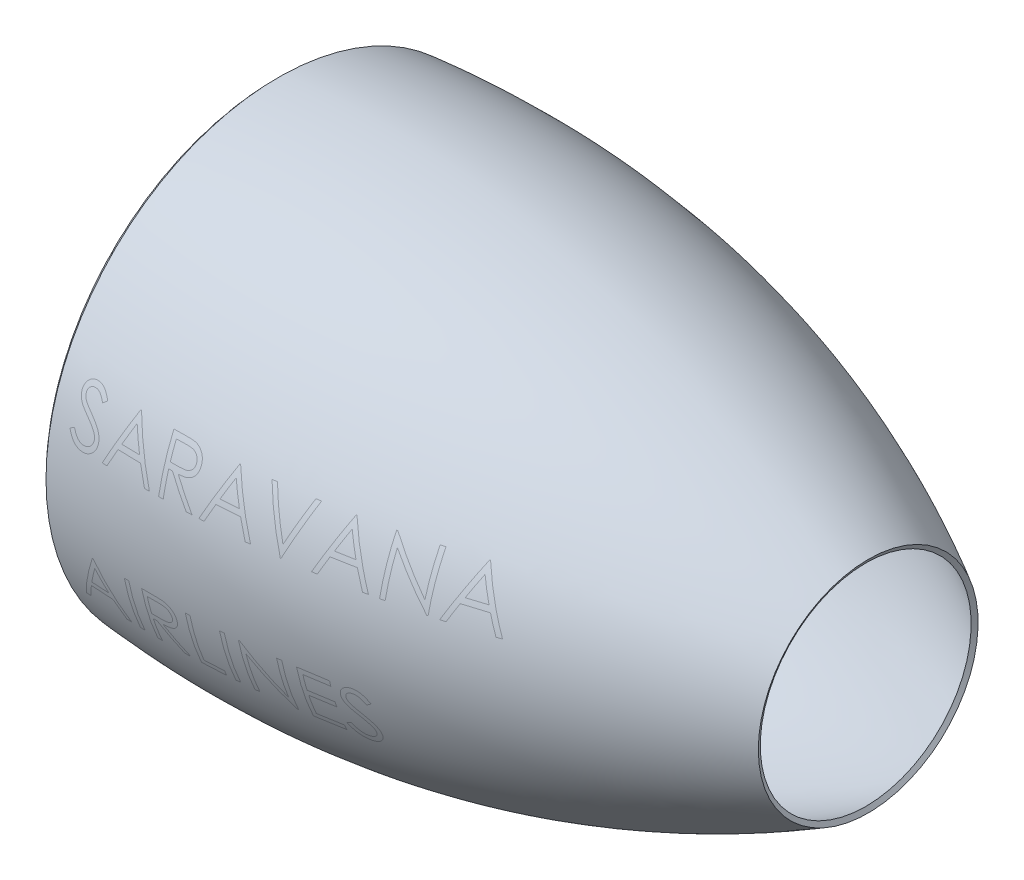
SolidWorks part; units mm, degrees
ref_plane "Front Plane" through (0, 0, 0) normal (0, 0, 1) x (1, 0, 0)
ref_plane "Top Plane" through (0, 0, 0) normal (0, 1, 0) x (1, 0, 0)
ref_plane "Right Plane" through (0, 0, 0) normal (1, 0, 0) x (0, 0, -1)
sketch "Sketch1" plane through (0, 0, 0) normal (0, 0, 1) x (1, 0, 0)
  line L0 (621.6787, 0) -> (0, 0) construction
  line L1 (0, 0) -> (0, 228.1541) construction
  line L2 (0, 180) -> (25, 180)
  line L3 (25, 180) -> (44.8479, 190)
  line L4 (44.8479, 190) -> (69.8479, 190)
  spline S0 degree 2 poles (0, 228.1541) (313.0954, 257.5885) (580, 108) knots 0 0 0 1 1 1
  spline S1 degree 2 poles (0, 228.1541) (-24.4685, 203.728) (0, 180) knots 0 0 0 1 1 1
  point P6 (-19.8945, 215.3986)
  point P12 (0, 228.1541)
  point P13 (-12.2246, 203.227)
  point P14 (390.041, 190)
  point P15 (44.8479, 190)
  dimension "D1" = 580
  dimension "D2" = 108
  dimension "D3" = 180
  dimension "D4" = 190
  dimension "D5" = 25
  dimension "D6" = 25
surface "Surface-Revolve1" sketch "Sketch1" parameters "D1"=360
thicken "Thicken1" surfaces to thicken 101 thickness 5 parameters "D1"=5
ref_plane "Plane1" through (0, 0, 250) normal (0, 0, 1) x (1, 0, 0)
sketch "Sketch2" plane through (0, 0, 250) normal (0, 0, 1) x (1, 0, 0)
  line L0 (18.0638, 41.8491) -> (534.2023, 41.8491) construction
  line L1 (18.0638, -95.3229) -> (534.2023, -95.3229) construction
  text T0 "SARAVANA" font "Century Gothic" height 50
  text T1 "AIRLINES" font "Century Gothic" height 50
split line "Split Line1"
